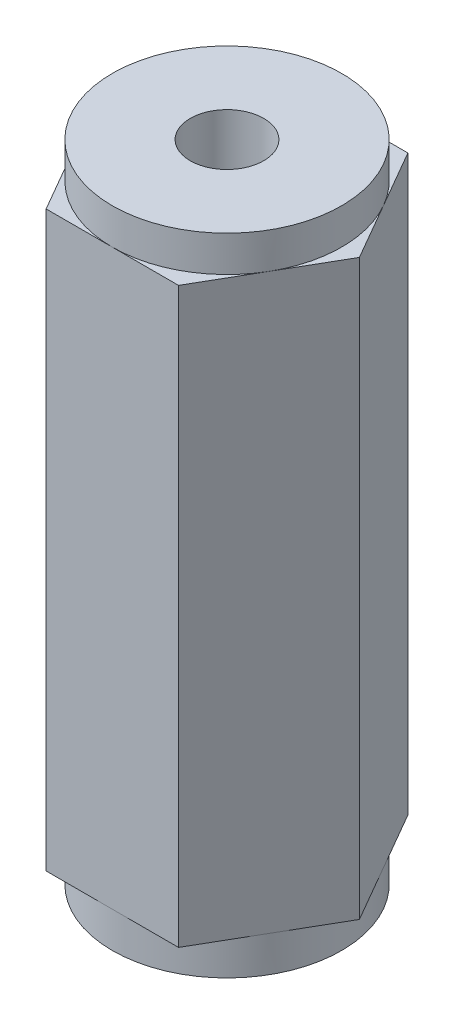
SolidWorks part; units mm, degrees
ref_plane "Front Plane" through (0, 0, 0) normal (0, 0, 1) x (1, 0, 0)
ref_plane "Top Plane" through (0, 0, 0) normal (0, 1, 0) x (1, 0, 0)
ref_plane "Right Plane" through (0, 0, 0) normal (1, 0, 0) x (0, 0, -1)
sketch "Sketch1" plane through (0, 0, 0) normal (0, 1, 0) x (1, 0, 0)
  line L1 (3.695, 0) -> (1.8475, 3.2)
  line L2 (1.8475, 3.2) -> (-1.8475, 3.2)
  line L3 (-1.8475, 3.2) -> (-3.695, 0)
  line L4 (-3.695, 0) -> (-1.8475, -3.2)
  line L5 (-1.8475, -3.2) -> (1.8475, -3.2)
  line L6 (1.8475, -3.2) -> (3.695, 0)
  circle A0 centre (0, 0) radius 3.2 construction
  dimension "D1" = 6.4
extrude "Boss-Extrude1" add sketch "Sketch1" along normal mid plane 18
sketch "Sketch3" plane through (0, 9, 0) normal (0, 1, 0) x (1, 0, 0)
  circle A0 centre (0, 0) radius 3.2
extrude "Cut-Extrude1" cut sketch "Sketch3" against normal blind 1 flip side to cut
mirror "Mirror2" about plane through (0, 0, 0) normal (0, 1, 0) of "Cut-Extrude1"
hole_wizard "M2.5 Tapped Hole1" positions "3DSketch1" profile "Sketch2" tap size "M2.5" standard "ISO"
sketch3d "3DSketch1"
  point P0 (0, 9, 0)
sketch "Sketch2" plane through (0, 9, 0) normal (1, 0, 0) x (0, 0, 1)
  line L0 (0, 0) -> (0, 6.9659)
  line L1 (0, 6.9659) -> (1.025, 6.35)
  line L2 (1.025, 6.35) -> (1.025, 0)
  line L5 (1.025, 0) -> (0, 0)
  line L10 (0, 6.9659) -> (-1.025, 6.35) construction
  line L11 (0, -6.35) -> (0, 107.95) construction
  dimension "Tap Drill Dia." = 2.05
  dimension "Tap Drill Depth" = 6.35
  dimension "Drill Angle" = 118
cosmetic thread "Hole Thread1" parameters "D1"=5, "D2"=2.5
mirror "Mirror1" about plane through (0, 0, 0) normal (0, 1, 0) of "M2.5 Tapped Hole1"
